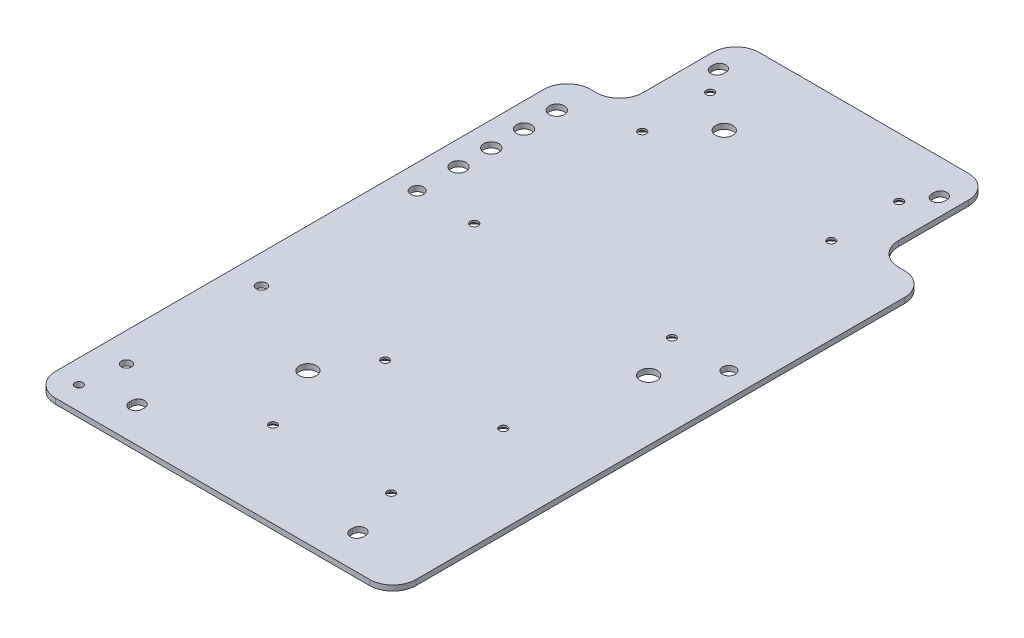
SolidWorks part; units mm, degrees
ref_plane "Front" through (0, 0, 0) normal (0, 0, 1) x (1, 0, 0)
ref_plane "Top" through (0, 0, 0) normal (0, 1, 0) x (1, 0, 0)
ref_plane "Right" through (0, 0, 0) normal (1, 0, 0) x (0, 0, -1)
sketch "Sketch1" plane through (0, 0, 0) normal (0, 1, 0) x (1, 0, 0)
  line L1 (-77.5, 140) -> (77.5, 140)
  line L2 (-77.5, 140) -> (-77.5, -140)
  line L3 (-77.5, -140) -> (77.5, -140)
  line L4 (77.5, 140) -> (77.5, -140)
  line L5 (-77.5, 140) -> (77.5, -140) construction
  line L6 (-77.5, -140) -> (77.5, 140) construction
  point P0 (0, 0)
  dimension "D1" = 155
  dimension "D2" = 280
extrude "Boss-Extrude1" add sketch "Sketch1" along normal mid plane 2.286
hole_wizard "M5 Clearance Hole1" positions "Sketch2" profile "Sketch4" hole size "M5" standard "ANSI Metric" end condition up to next
sketch "Sketch2" plane through (0, 1.143, 0) normal (0, 1, 0) x (1, 0, 0)
  line L1 (-47.5, 125) -> (47.5, 125)
  line L2 (-47.5, 125) -> (-47.5, -125)
  line L3 (-47.5, -125) -> (47.5, -125)
  line L4 (47.5, 125) -> (47.5, -125)
  line L5 (-47.5, 125) -> (47.5, -125) construction
  line L6 (-47.5, -125) -> (47.5, 125) construction
  line L7 (-67, 15) -> (67, 15) construction
  line L8 (0, 15) -> (0, 0) construction
  point P2 (47.5, -125)
  point P67 (-47.5, 125)
  point P68 (-47.5, -125)
  point P69 (47.5, 125)
  point P82 (67, 15)
  point P107 (-67, 15)
  dimension "D1" = 95
  dimension "D2" = 250
  dimension "D3" = 134
  dimension "D4" = 15
sketch "Sketch4" plane through (47.5, 1.143, 125) normal (1, 0, 0) x (0, 0, 1)
  line L0 (0, 0) -> (0, 2.286)
  line L1 (0, 2.286) -> (2.75, 2.286)
  line L2 (2.75, 2.286) -> (2.75, 0)
  line L5 (2.75, 0) -> (0, 0)
  line L11 (0, -6.35) -> (0, 107.95) construction
  dimension "Thru Hole Dia." = 5.5
  dimension "Thru Hole Depth" = 2.286
hole_wizard "Top Side M3 Flat Head" positions "Sketch5" profile "Sketch7" countersink size "M3" standard "ANSI Metric" end condition up to next
sketch "Sketch5" plane through (0, -1.143, 0) normal (0, -1, 0) x (-1, 0, 0)
  line L0 (-42.5, 15) -> (42.5, 15) construction
  line L2 (-40, -103.2) -> (10.8, -103.2)
  line L3 (-40, -103.2) -> (-40, -55)
  line L4 (-40, -55) -> (10.8, -55)
  line L5 (10.8, -103.2) -> (10.8, -55)
  line L6 (-40, -103.2) -> (10.8, -55) construction
  line L7 (-40, -55) -> (10.8, -103.2) construction
  line L9 (-40.64, 85.395) -> (40.64, 85.395)
  line L10 (-40.64, 85.395) -> (-40.64, 114.605)
  line L11 (-40.64, 114.605) -> (40.64, 114.605)
  line L12 (40.64, 85.395) -> (40.64, 114.605)
  line L13 (-40.64, 85.395) -> (40.64, 114.605) construction
  line L14 (-40.64, 114.605) -> (40.64, 85.395) construction
  line L15 (0, 0) -> (0, 15) construction
  line L16 (0, 100) -> (0, 15) construction
  point P0 (-42.5, 15)
  point P4 (42.5, 15)
  point P15 (10.8, -55)
  point P74 (-40, -103.2)
  point P75 (-40, -55)
  point P76 (10.8, -103.2)
  point P88 (40.64, 114.605)
  point P255 (-40.64, 85.395)
  point P256 (-40.64, 114.605)
  point P257 (40.64, 85.395)
  dimension "D1" = 85
  dimension "D2" = 15
  dimension "D3" = 48.2
  dimension "D4" = 50.8
  dimension "D5" = 55
  dimension "D6" = 40
  dimension "D7" = 100
  dimension "D8" = 29.21
  dimension "D9" = 81.28
sketch "Sketch7" plane through (42.5, -1.143, -15) normal (1, 0, 0) x (0, 0, -1)
  line L0 (0, 0) -> (0, 2.286)
  line L1 (0, 2.286) -> (1.7, 2.286)
  line L2 (1.7, 2.286) -> (1.7, 1.45)
  line L3 (1.7, 1.45) -> (3.15, 0)
  line L5 (3.15, 0) -> (0, 0)
  line L6 (-1.7, 1.45) -> (-3.15, 0) construction
  line L11 (0, -6.35) -> (0, 107.95) construction
  dimension "Thru Hole Dia." = 3.4
  dimension "Thru Hole Depth" = 2.286
  dimension "Near C'Sink Dia." = 6.3
  dimension "Near C'Sink Angle" = 90
hole_wizard "Router M3 Mounting" positions "Sketch8" profile "Sketch9" hole size "Ø7.4" standard "ANSI Metric" end condition up to next
sketch "Sketch8" plane through (0, 1.143, 0) normal (0, 1, 0) x (1, 0, 0)
  line L8 (60, 114) -> (-60, 114)
  line L9 (60, 114) -> (60, -114)
  line L10 (60, -114) -> (-60, -114)
  line L11 (-60, 114) -> (-60, -114)
  line L12 (60, 114) -> (-60, -114) construction
  line L13 (60, -114) -> (-60, 114) construction
  line L14 (-23.5, 103.5) -> (-23.5, -75.5) construction
  line L15 (47.5, 125) -> (47.5, -125) construction
  line L16 (47.5, -125) -> (0, 0) construction
  line L17 (0, 0) -> (47.5, 0) construction
  line L18 (47.5, 125) -> (-47.5, 125) construction
  line L20 (0, 0) -> (0, 125) construction
  point P129 (-23.5, 103.5)
  point P131 (51.5, -4)
  point P133 (-23.5, -75.5)
  dimension "D1" = 36.5
  dimension "D2" = 10.5
  dimension "D3" = 110
  dimension "D4" = 8.5
  dimension "D5" = 38.5
  dimension "D6" = 228
  dimension "D7" = 120
sketch "Sketch9" plane through (-23.5, 1.143, 75.5) normal (1, 0, 0) x (0, 0, 1)
  line L0 (0, 0) -> (0, 2.286)
  line L1 (0, 2.286) -> (3.7, 2.286)
  line L2 (3.7, 2.286) -> (3.7, 0)
  line L5 (3.7, 0) -> (0, 0)
  line L11 (0, -6.35) -> (0, 107.95) construction
  dimension "Thru Hole Dia." = 7.4
  dimension "Thru Hole Depth" = 2.286
sketch "Sketch10" plane through (0, 1.143, 0) normal (0, 1, 0) x (1, 0, 0)
  line L1 (-77.5, 140) -> (-55, 140)
  line L2 (-77.5, 140) -> (-77.5, 90)
  line L3 (-77.5, 90) -> (-55, 90)
  line L4 (-55, 140) -> (-55, 90)
  line L5 (77.5, 140) -> (55, 140)
  line L6 (77.5, 140) -> (77.5, 90)
  line L7 (77.5, 90) -> (55, 90)
  line L8 (55, 140) -> (55, 90)
  dimension "D1" = 50
  dimension "D2" = 55
extrude "Cut-Extrude1" cut sketch "Sketch10" against normal up to next
fillet "Fillet1" radius 10 8 edges at (-77.5, 0, -90) (-77.5, 0, 140) (77.5, 0, 140) (77.5, 0, -90) (55, 0, -90) (55, 0, -140) (-55, 0, -90) (-55, 0, -140)
hole_wizard "Power Terminal Blocks M2.5 Inserts" positions "Sketch11" profile "Sketch12" hole size "Ø4.4" standard "ANSI Metric" end condition up to next
sketch "Sketch11" plane through (0, 1.143, 0) normal (0, 1, 0) x (1, 0, 0)
  line L7 (-65, -112) -> (-65, -54) construction
  point P119 (-65, -112)
  point P120 (-65, -54)
  dimension "D1" = 65
  dimension "D2" = 54
  dimension "D5" = 58
sketch "Sketch12" plane through (-65, 1.143, 112) normal (1, 0, 0) x (0, 0, 1)
  line L0 (0, 0) -> (0, 2.286)
  line L1 (0, 2.286) -> (2.2, 2.286)
  line L2 (2.2, 2.286) -> (2.2, 0)
  line L5 (2.2, 0) -> (0, 0)
  line L11 (0, -6.35) -> (0, 107.95) construction
  dimension "Thru Hole Dia." = 4.4
  dimension "Thru Hole Depth" = 2.286
hole_wizard "M3 grounding wire hole" positions "Sketch13" profile "Sketch14" hole size "M3" standard "ANSI Metric" end condition up to next
sketch "Sketch13" plane through (0, 1.143, 0) normal (0, 1, 0) x (1, 0, 0)
  point P0 (-67.5, -130)
sketch "Sketch14" plane through (-67.5, 1.143, 130) normal (1, 0, 0) x (0, 0, 1)
  line L0 (0, 0) -> (0, 2.286)
  line L1 (0, 2.286) -> (1.7, 2.286)
  line L2 (1.7, 2.286) -> (1.7, 0)
  line L5 (1.7, 0) -> (0, 0)
  line L11 (0, -6.35) -> (0, 107.95) construction
  dimension "Thru Hole Dia." = 3.4
  dimension "Thru Hole Depth" = 2.286
sketch "Sketch15" plane through (0, 1.143, 0) normal (0, 1, 0) x (1, 0, 0)
  line L0 (47.5, 124.5) -> (47.5, 125.5) construction
  line L1 (44.75, 124.5) -> (44.75, 125.5)
  line L2 (50.25, 124.5) -> (50.25, 125.5)
  line L3 (-47.5, 125.5) -> (-47.5, 124.5) construction
  line L4 (-44.75, 125.5) -> (-44.75, 124.5)
  line L5 (-50.25, 125.5) -> (-50.25, 124.5)
  line L6 (-47.5, -124.5) -> (-47.5, -125.5) construction
  line L7 (-44.75, -124.5) -> (-44.75, -125.5)
  line L8 (-50.25, -124.5) -> (-50.25, -125.5)
  line L9 (47.5, -124.5) -> (47.5, -125.5) construction
  line L10 (50.25, -124.5) -> (50.25, -125.5)
  line L11 (44.75, -124.5) -> (44.75, -125.5)
  arc A0 (44.75, 124.5) -> (50.25, 124.5) centre (47.5, 124.5) ccw
  arc A1 (50.25, 125.5) -> (44.75, 125.5) centre (47.5, 125.5) ccw
  circle A2 centre (47.5, 125) radius 2.75 construction
  arc A3 (-44.75, 125.5) -> (-50.25, 125.5) centre (-47.5, 125.5) ccw
  arc A4 (-50.25, 124.5) -> (-44.75, 124.5) centre (-47.5, 124.5) ccw
  arc A5 (-44.75, -124.5) -> (-50.25, -124.5) centre (-47.5, -124.5) ccw
  arc A6 (-50.25, -125.5) -> (-44.75, -125.5) centre (-47.5, -125.5) ccw
  arc A7 (50.25, -124.5) -> (44.75, -124.5) centre (47.5, -124.5) ccw
  arc A8 (44.75, -125.5) -> (50.25, -125.5) centre (47.5, -125.5) ccw
  point P2 (47.5, 125)
  point P12 (-47.5, 125)
  point P19 (-47.5, -125)
  point P27 (47.5, -125)
  dimension "D1" = 1
extrude "Cut-Extrude2" cut sketch "Sketch15" against normal up to next
sketch "Sketch17" plane through (0, 1.143, 0) normal (0, 1, 0) x (1, 0, 0)
  line L0 (-67, 17.75) -> (-67, 90) construction
  line L1 (-67.5, 90) -> (-65, 90) construction
  circle A0 centre (-67, 32.75) radius 3.25
  circle A1 centre (-67, 15) radius 2.75 construction
  circle A2 centre (-67, 46.8333) radius 3.25
  circle A3 centre (-67, 60.9167) radius 3.25
  circle A4 centre (-67, 75) radius 3.25
  point P2 (-67, 15)
  point P3 (-67, 67.5173)
  point P17 (-67, 27.8002)
  dimension "D2" = 6.5
  dimension "D3" = 15
  dimension "D4" = 15
  dimension "D1" = 4
extrude "Cut-Extrude3" cut sketch "Sketch17" against normal up to next
